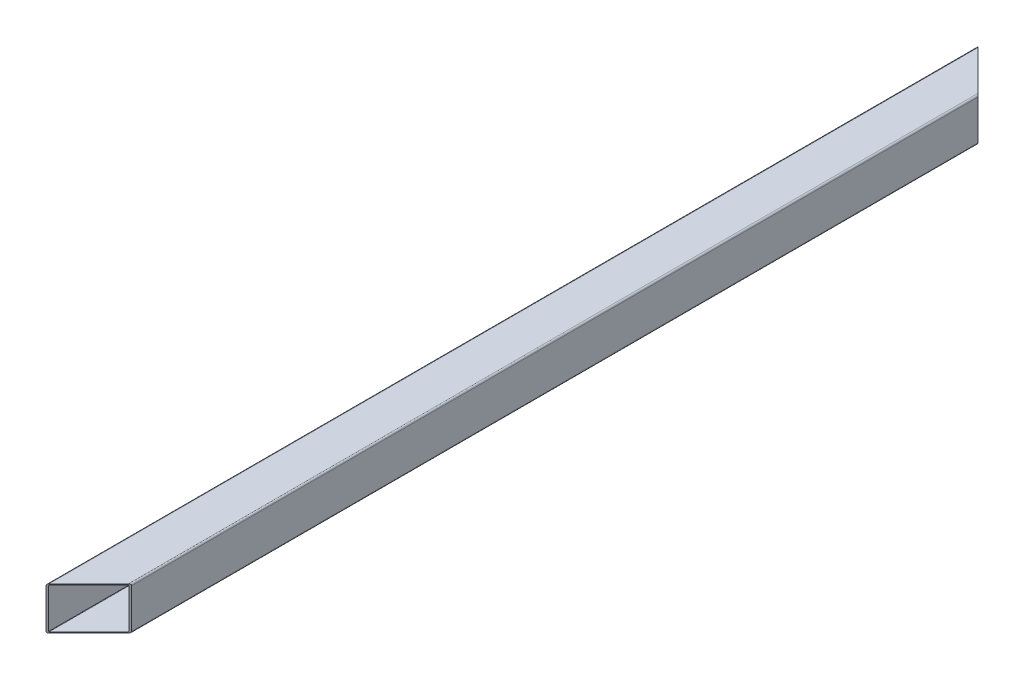
SolidWorks part; units mm, degrees
material "AISI 1020 Steel, Cold Rolled"
ref_plane "Front Plane" through (0, 0, 0) normal (0, 0, 1) x (1, 0, 0)
ref_plane "Top Plane" through (0, 0, 0) normal (0, 1, 0) x (1, 0, 0)
ref_plane "Right Plane" through (0, 0, 0) normal (1, 0, 0) x (0, 0, -1)
sketch "Sketch1" plane through (0, 0, 0) normal (0, 1, 0) x (1, 0, 0)
  line L0 (0, 0) -> (0, 870)
  dimension "D1" = 870
other "Structural Member1"
ref_plane "Plane1" through (0, 0, 0) normal (0, 0, -1) x (-1, 0, 0)
sketch "Sketch12" plane through (0, 0, 0) normal (0, 0, -1) x (-1, 0, 0)
  line L0 (-18.5, -18.8) -> (18.5, -18.8)
  line L1 (-18.8, -18.5) -> (-18.8, 18.5)
  line L2 (18.5, 18.8) -> (-18.5, 18.8)
  line L3 (18.8, 18.5) -> (18.8, -18.5)
  line L4 (-18.5, -20) -> (18.5, -20)
  line L5 (-20, -18.5) -> (-20, 18.5)
  line L6 (18.5, 20) -> (-18.5, 20)
  line L7 (20, 18.5) -> (20, -18.5)
  arc A0 (20, 18.5) -> (18.5, 20) centre (18.5, 18.5) ccw
  arc A1 (18.5, -20) -> (20, -18.5) centre (18.5, -18.5) ccw
  arc A2 (-20, -18.5) -> (-18.5, -20) centre (-18.5, -18.5) ccw
  arc A3 (-18.5, 20) -> (-20, 18.5) centre (-18.5, 18.5) ccw
  arc A4 (-18.5, 18.8) -> (-18.8, 18.5) centre (-18.5, 18.5) ccw
  arc A5 (18.8, 18.5) -> (18.5, 18.8) centre (18.5, 18.5) ccw
  arc A6 (18.5, -18.8) -> (18.8, -18.5) centre (18.5, -18.5) ccw
  arc A7 (-18.8, -18.5) -> (-18.5, -18.8) centre (-18.5, -18.5) ccw
  point P0 (-20, 0)
  point P1 (20, 0)
  point P2 (0, 20)
  point P3 (0, -20)
  point P4 (0, 0)
  point P5 (-20, -20)
  point P6 (20, -20)
  point P7 (20, 20)
  point P8 (-20, 20)
  point P33 (0, 0)
  dimension "D1" = 1.5
  dimension "Thickness" = 1.2
  dimension "V_leg" = 40
ref_plane "Plane2" through (0, 50, 0) normal (0, 1, 0) x (1, 0, 0)
sketch "Sketch14" plane through (0, 50, 0) normal (0, 1, 0) x (1, 0, 0)
  line L0 (-20, 870) -> (54.1651, 795.8349)
  line L1 (54.1651, 795.8349) -> (54.1651, 870)
  line L2 (54.1651, 870) -> (-20, 870)
  line L3 (-20, 0) -> (47.8238, 67.8238)
  line L4 (47.8238, 67.8238) -> (47.8238, 0)
  line L5 (-20, 0) -> (47.8238, 0)
extrude "Cut-Extrude2" cut sketch "Sketch14" against normal blind 375
